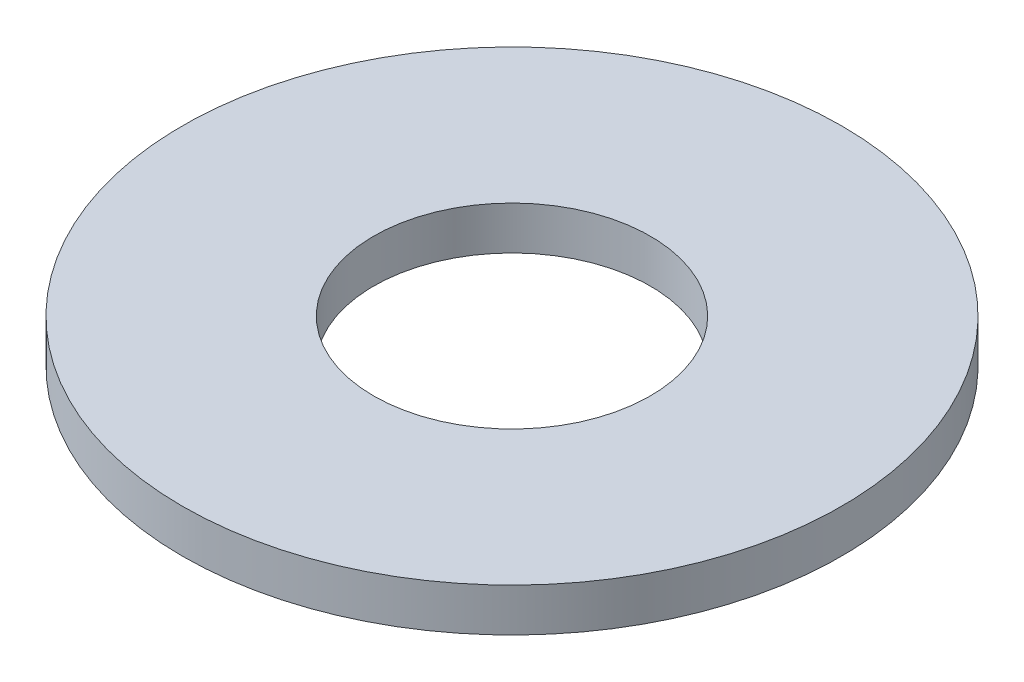
SolidWorks part; units mm, degrees
ref_plane "Front Plane" through (0, 0, 0) normal (0, 0, 1) x (1, 0, 0)
ref_plane "Top Plane" through (0, 0, 0) normal (0, 1, 0) x (1, 0, 0)
ref_plane "Right Plane" through (0, 0, 0) normal (1, 0, 0) x (0, 0, -1)
sketch "Sketch1" plane through (0, 0, 0) normal (0, 1, 0) x (1, 0, 0)
  circle A0 centre (0, 0) radius 38.1
extrude "Boss-Extrude1" add sketch "Sketch1" along normal blind 5
sketch "Sketch2" plane through (0, 5, 0) normal (0, 1, 0) x (1, 0, 0)
  circle A0 centre (0, 0) radius 16
extrude "Cut-Extrude1" cut sketch "Sketch2" against normal blind 5
